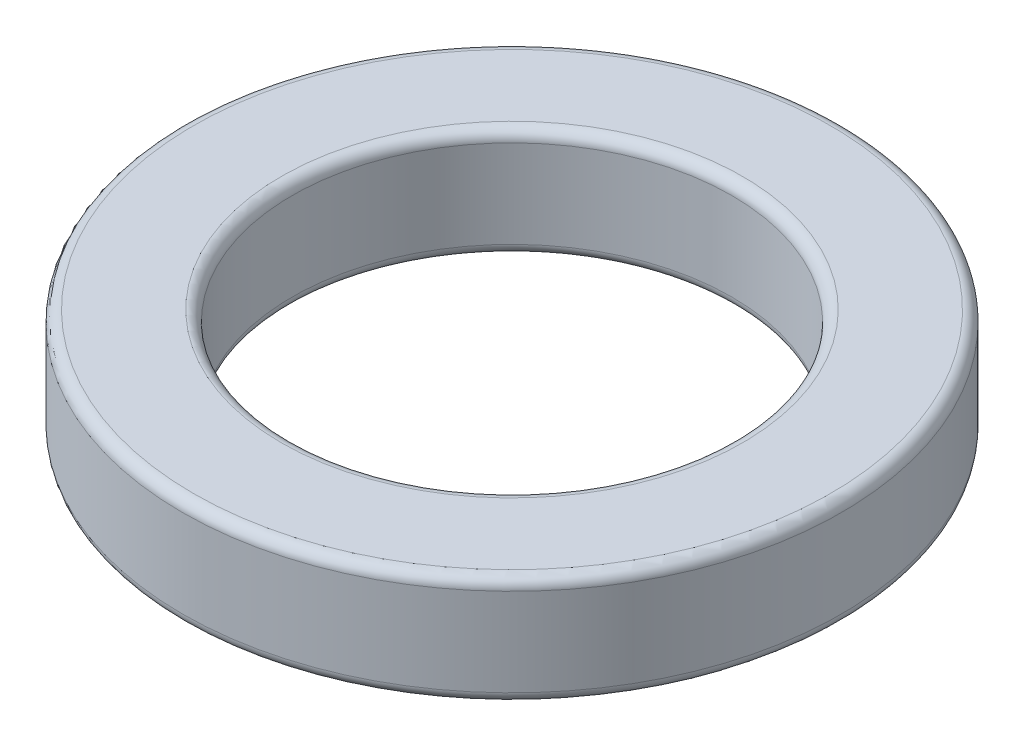
SolidWorks part; units mm, degrees
ref_plane "前视基准面" through (0, 0, 0) normal (0, 0, 1) x (1, 0, 0)
ref_plane "上视基准面" through (0, 0, 0) normal (0, 1, 0) x (1, 0, 0)
ref_plane "右视基准面" through (0, 0, 0) normal (1, 0, 0) x (0, 0, -1)
sketch "Sketch1" plane through (0, 0, 0) normal (0, 1, 0) x (1, 0, 0)
  circle A0 centre (0, 0) radius 3
  circle A1 centre (0, 0) radius 2
  dimension "D1" = 4
  dimension "D2" = 6
extrude "Boss-Extrude1" add sketch "Sketch1" along normal blind 1
fillet "Fillet1" radius 0.1 4 edges at (0, 0, 2) (0, 1, 2) (0, 0, 3) (0, 1, 3)
